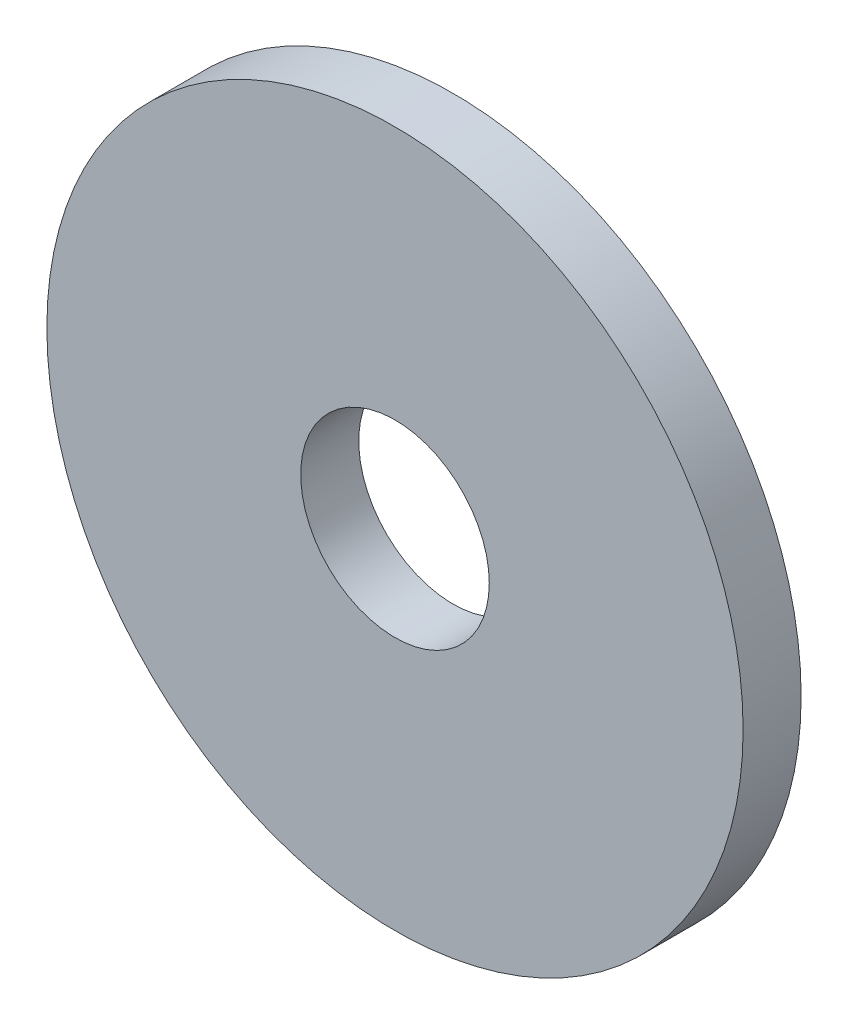
SolidWorks part; units mm, degrees
ref_plane "Plano frontal" through (0, 0, 0) normal (0, 0, 1) x (1, 0, 0)
ref_plane "Plano superior" through (0, 0, 0) normal (0, 1, 0) x (1, 0, 0)
ref_plane "Plano direito" through (0, 0, 0) normal (1, 0, 0) x (0, 0, -1)
sketch "Esboço1" plane through (0, 0, 0) normal (0, 0, 1) x (1, 0, 0)
  circle A0 centre (0, 0) radius 1.625
  circle A1 centre (0, 0) radius 6
  dimension "D1" = 3.25
  dimension "D2" = 12
extrude "Ressalto-extrusão1" add sketch "Esboço1" along normal blind 1
